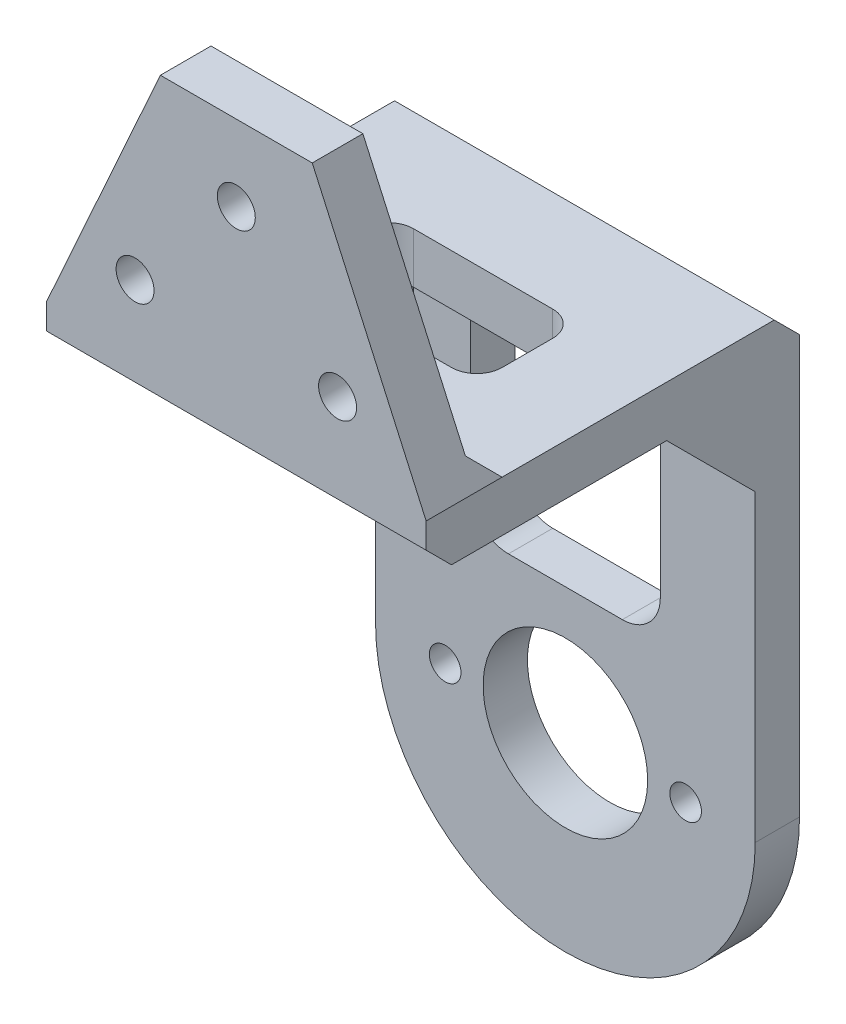
SolidWorks part; units mm, degrees
material "6061 合金"
ref_plane "前视基准面" through (0, 0, 0) normal (0, 0, 1) x (1, 0, 0)
ref_plane "上视基准面" through (0, 0, 0) normal (0, 1, 0) x (1, 0, 0)
ref_plane "右视基准面" through (0, 0, 0) normal (1, 0, 0) x (0, 0, -1)
sketch "草图1" plane through (0, 0, 0) normal (0, 0, 1) x (1, 0, 0)
  line L0 (0, 0) -> (0, 28) construction
  line L1 (-7.5, 28) -> (7.5, 28)
  line L2 (7.5, 28) -> (7.5, 10)
  line L3 (-15, 35) -> (15, 35)
  line L4 (15, 35) -> (15, 0)
  line L5 (0, 0) -> (0, 54.5291) construction
  line L6 (-15, 35) -> (-15, 0)
  line L7 (-7.5, 28) -> (-7.5, 10)
  line L8 (9.5, 0) -> (9.5, 18.0398) construction
  line L9 (7.5, 10) -> (-7.5, 10)
  line L10 (-9, -9) -> (9, -9) construction
  line L11 (-9, -9) -> (-9, 9) construction
  line L12 (-9, 9) -> (9, 9) construction
  line L13 (9, -9) -> (9, 9) construction
  line L14 (-9, -9) -> (9, 9) construction
  line L15 (-9, 9) -> (9, -9) construction
  arc A1 (-15, 0) -> (15, 0) centre (0, 0) ccw
  circle A2 centre (0, 0) radius 9.5 construction
  circle A3 centre (0, -9.5) radius 1.25 construction
  circle A4 centre (-9.5, 0) radius 1.25 construction
  circle A5 centre (0, 9.5) radius 1.25 construction
  circle A6 centre (9.5, 0) radius 1.25 construction
  circle A7 centre (10.5, 15.45) radius 1.3 construction
  circle A8 centre (-10.5, 15.45) radius 1.3 construction
  circle A9 centre (0, 0) radius 6.5
  point P13 (0, 35)
  point P24 (0, 0)
  dimension "D2" = 30
  dimension "D3" = 35
  dimension "D5" = 19
  dimension "D6" = 2.5
  dimension "D8" = 2.6
  dimension "D9" = 15.45
  dimension "D4" = 13
  dimension "D10" = 18
  dimension "D11" = 18
  dimension "D12" = 10
  dimension "D13" = 15
  dimension "D14" = 18
  dimension "D15" = 1
  dimension "D7" = 4
extrude "凸台-拉伸1" add sketch "草图1" along normal blind 3.5
hole_wizard "M3 螺纹孔1" positions "草图8" profile "草图9" tap size "M3" standard "GB"
sketch "草图8" plane through (0, 0, 3.5) normal (0, 0, 1) x (1, 0, 0)
  point P0 (9.5, 0)
  point P3 (-9.5, 0)
  point P7 (0, -9.5)
sketch "草图9" plane through (9.5, 0, 3.5) normal (1, 0, 0) x (0, -1, 0)
  line L0 (0, 0) -> (0, 3.5)
  line L1 (0, 3.5) -> (1.25, 3.5)
  line L2 (1.25, 3.5) -> (1.25, 0)
  line L5 (1.25, 0) -> (0, 0)
  line L11 (0, -6.35) -> (0, 107.95) construction
  dimension "通孔螺纹孔钻头直径" = 2.5
  dimension "通孔螺纹孔钻头深度" = 3.5
cosmetic thread "孔螺纹线1" parameters "D2"=3
cosmetic thread "孔螺纹线2" parameters "D2"=3
fillet "圆角1" radius 3 4 edges at (-7.5, 10, 1.75) (7.5, 10, 1.75) (7.5, 28, 1.75) (-7.5, 28, 1.75)
sketch "草图2" plane through (15, 0, 0) normal (1, 0, 0) x (0, 0, -1)
  line L1 (-3.5, 35) -> (-29.5, 35)
  line L2 (-3.5, 35) -> (-3.5, 31)
  line L3 (-3.5, 31) -> (-29.5, 31)
  line L4 (-29.5, 35) -> (-29.5, 31)
  dimension "D1" = 26
  dimension "D2" = 4
extrude "凸台-拉伸2" add sketch "草图2" against normal through all
sketch "草图4" plane through (0, 0, 29.5) normal (0, 0, 1) x (1, 0, 0)
  line L0 (0, 0) -> (0, 68.5743) construction
  line L1 (-15, 35) -> (-6, 55)
  line L2 (-6, 55) -> (6, 55)
  line L3 (-15, 35) -> (15, 35)
  line L4 (15, 35) -> (6, 55)
  line L5 (-4.5, 55) -> (-4.5, 35) construction
  line L6 (4.5, 55) -> (4.5, 35) construction
  line L7 (-15, 35) -> (15, 35) construction
  circle A0 centre (0, 49) radius 1.5
  circle A1 centre (-8, 40) radius 1.5
  circle A2 centre (8, 40) radius 1.5
  point P9 (0, 35)
  point P10 (0, 55)
  dimension "D3" = 3
  dimension "D4" = 14
  dimension "D5" = 3
  dimension "D6" = 8
  dimension "D7" = 5
  dimension "D1" = 20
  dimension "D2" = 12
  dimension "D8" = 4.5
extrude "凸台-拉伸3" add sketch "草图4" against normal blind 4
chamfer "倒角1" distance 2 angle 45 4 edges at (0, 35, 25.5) (0, 31, 29.5) (0, 31, 3.5) (0, 35, 0)
sketch "草图5" plane through (0, 35, 0) normal (0, 1, 0) x (1, 0, 0)
  line L0 (0, 0) -> (0, -20.9446) construction
  line L1 (-15, 0) -> (15, 0) construction
  line L2 (7.5, -10) -> (-7.5, -10)
  line L3 (7.5, -10) -> (7.5, -18)
  line L4 (7.5, -18) -> (-7.5, -18)
  line L5 (-7.5, -10) -> (-7.5, -18)
  line L6 (7.5, -10) -> (-7.5, -18) construction
  line L7 (7.5, -18) -> (-7.5, -10) construction
  point P3 (0, -14)
  dimension "D1" = 15
  dimension "D2" = 8
  dimension "D3" = 10
extrude "切除-拉伸1" cut sketch "草图5" against normal blind 10
fillet "圆角2" radius 2 4 edges at (7.5, 33, 10) (-7.5, 33, 10) (-7.5, 33, 18) (7.5, 33, 18)
sketch "草图6" plane through (-15, 0, 0) normal (-1, 0, 0) x (0, 0, 1)
  line L0 (3.5, 24) -> (10.5, 31)
  line L1 (3.5, 29) -> (3.5, 0) construction
  line L2 (27.5, 31) -> (5.5, 31) construction
  line L3 (10.5, 31) -> (5.5, 31)
  line L4 (5.5, 31) -> (3.5, 29)
  line L5 (3.5, 29) -> (3.5, 24)
  dimension "D1" = 5
extrude "凸台-拉伸4" add sketch "草图6" against normal blind 3
sketch "草图7" plane through (15, 0, 0) normal (1, 0, 0) x (0, 0, -1)
  line L0 (-3.5, 0) -> (-3.5, 29) construction
  line L1 (-5.5, 31) -> (-3.5, 29) construction
  line L2 (-27.5, 31) -> (-5.5, 31) construction
  line L3 (-3.5, 24) -> (-10.5, 31) construction
  line L4 (-3.5, 24) -> (-3.5, 29)
  line L5 (-5.5, 31) -> (-3.5, 29)
  line L6 (-10.5, 31) -> (-5.5, 31)
  line L7 (-3.5, 24) -> (-10.5, 31)
extrude "凸台-拉伸5" add sketch "草图7" against normal blind 3
